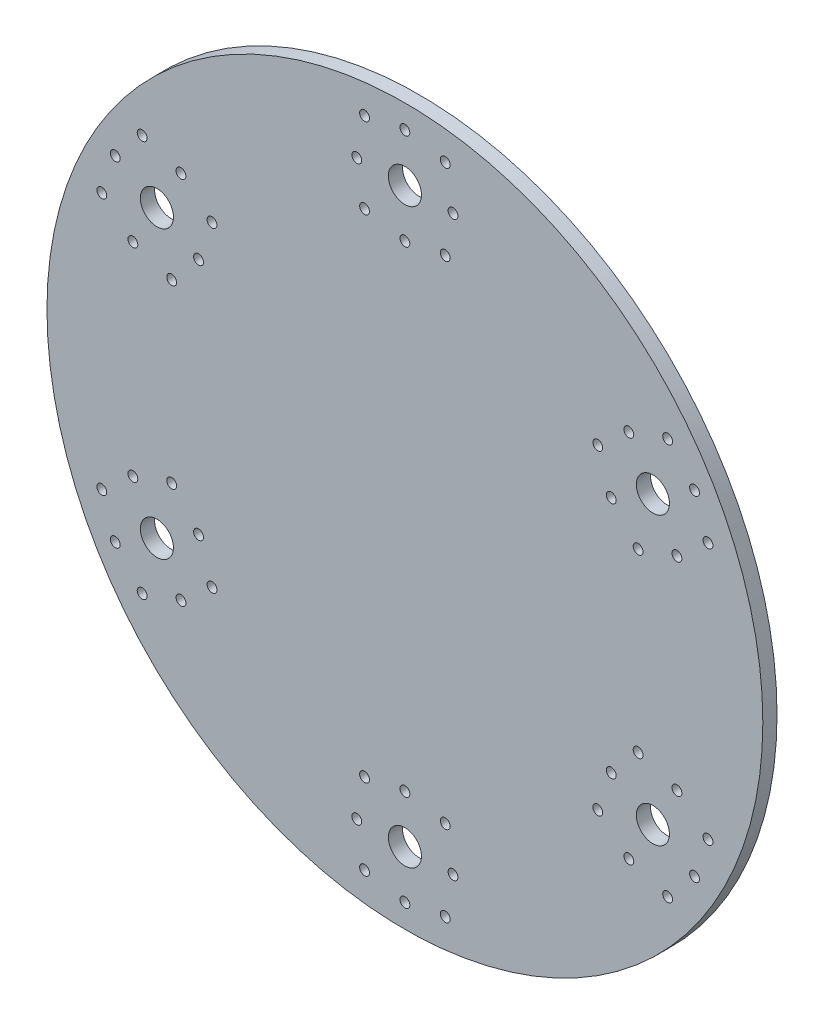
SolidWorks part; units mm, degrees
ref_plane "Front Plane" through (0, 0, 0) normal (0, 0, 1) x (1, 0, 0)
ref_plane "Top Plane" through (0, 0, 0) normal (0, 1, 0) x (1, 0, 0)
ref_plane "Right Plane" through (0, 0, 0) normal (1, 0, 0) x (0, 0, -1)
sketch "Sketch1" plane through (0, 0, 0) normal (0, 0, 1) x (1, 0, 0)
  circle A0 centre (0, 0) radius 80
  circle A1 centre (58.7256, 44.3156) radius 1.1
  circle A2 centre (67.7412, 28.7001) radius 1.1
  circle A3 centre (64.7354, 37.375) radius 1.1
  circle A4 centre (50.0506, 41.3098) radius 1.1
  circle A5 centre (52.1257, 19.6844) radius 1.1
  circle A6 centre (43.1101, 35.2999) radius 1.1
  circle A7 centre (60.8006, 22.6902) radius 1.1
  circle A8 centre (46.1159, 26.625) radius 1.1
  circle A9 centre (55.4256, 32) radius 3.7
  circle A10 centre (-10.75, 64) radius 1.1
  circle A11 centre (-9.0156, 73.0156) radius 1.1
  circle A12 centre (9.0156, 73.0156) radius 1.1
  circle A13 centre (9.0156, 54.9844) radius 1.1
  circle A14 centre (-9.0156, 54.9844) radius 1.1
  circle A15 centre (0, 74.75) radius 1.1
  circle A16 centre (10.75, 64) radius 1.1
  circle A17 centre (0, 53.25) radius 1.1
  circle A18 centre (0, 64) radius 3.7
  circle A19 centre (67.7412, -28.7001) radius 1.1
  circle A20 centre (58.7256, -44.3156) radius 1.1
  circle A21 centre (64.7354, -37.375) radius 1.1
  circle A22 centre (60.8006, -22.6902) radius 1.1
  circle A23 centre (43.1101, -35.2999) radius 1.1
  circle A24 centre (52.1257, -19.6844) radius 1.1
  circle A25 centre (50.0506, -41.3098) radius 1.1
  circle A26 centre (46.1159, -26.625) radius 1.1
  circle A27 centre (55.4256, -32) radius 3.7
  circle A28 centre (9.0156, -73.0156) radius 1.1
  circle A29 centre (-9.0156, -73.0156) radius 1.1
  circle A30 centre (0, -74.75) radius 1.1
  circle A31 centre (10.75, -64) radius 1.1
  circle A32 centre (-9.0156, -54.9844) radius 1.1
  circle A33 centre (9.0156, -54.9844) radius 1.1
  circle A34 centre (-10.75, -64) radius 1.1
  circle A35 centre (0, -53.25) radius 1.1
  circle A36 centre (0, -64) radius 3.7
  circle A37 centre (-58.7256, -44.3156) radius 1.1
  circle A38 centre (-67.7412, -28.7001) radius 1.1
  circle A39 centre (-64.7354, -37.375) radius 1.1
  circle A40 centre (-50.0506, -41.3098) radius 1.1
  circle A41 centre (-52.1257, -19.6844) radius 1.1
  circle A42 centre (-43.1101, -35.2999) radius 1.1
  circle A43 centre (-60.8006, -22.6902) radius 1.1
  circle A44 centre (-46.1159, -26.625) radius 1.1
  circle A45 centre (-55.4256, -32) radius 3.7
  circle A46 centre (-67.7412, 28.7001) radius 1.1
  circle A47 centre (-58.7256, 44.3156) radius 1.1
  circle A48 centre (-64.7354, 37.375) radius 1.1
  circle A49 centre (-60.8006, 22.6902) radius 1.1
  circle A50 centre (-43.1101, 35.2999) radius 1.1
  circle A51 centre (-52.1257, 19.6844) radius 1.1
  circle A52 centre (-50.0506, 41.3098) radius 1.1
  circle A53 centre (-46.1159, 26.625) radius 1.1
  circle A54 centre (-55.4256, 32) radius 3.7
  point P17 (55.4256, 32)
  point P22 (55.4256, 32)
  point P36 (0, 64)
  point P41 (0, 64)
  point P44 (0, 64)
  point P45 (0, 64)
  point P47 (55.4256, 32)
  point P48 (55.4256, 32)
  point P61 (55.4256, -32)
  point P66 (55.4256, -32)
  point P69 (55.4256, -32)
  point P70 (55.4256, -32)
  point P83 (0, -64)
  point P88 (0, -64)
  point P91 (0, -64)
  point P92 (0, -64)
  point P105 (-55.4256, -32)
  point P110 (-55.4256, -32)
  point P113 (-55.4256, -32)
  point P114 (-55.4256, -32)
  point P127 (-55.4256, 32)
  point P132 (-55.4256, 32)
  point P135 (-55.4256, 32)
  point P136 (-55.4256, 32)
  point P138 (0, 0)
  dimension "D1" = 160
  dimension "D2" = 10.75
  dimension "D4" = 10.75
  dimension "D5" = 10.75
  dimension "D6" = 64
  dimension "D3" = 7.4
  dimension "D8" = 2.2
  dimension "D11" = 9.0156
  dimension "D7" = 9.0156
  dimension "D10" = 12.75
  dimension "D12" = 45
  dimension "D13" = 6
  dimension "D9" = 10.75
extrude "Boss-Extrude2" add sketch "Sketch1" along normal blind 3.175
